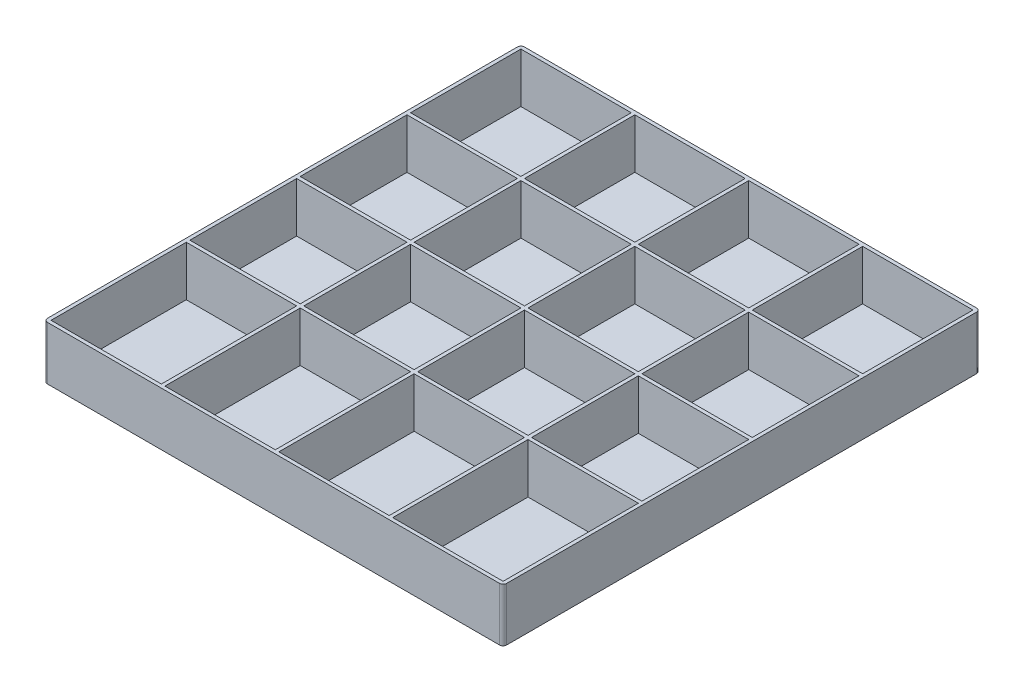
SolidWorks part; units mm, degrees
ref_plane "前视基准面" through (0, 0, 0) normal (0, 0, 1) x (1, 0, 0)
ref_plane "上视基准面" through (0, 0, 0) normal (0, 1, 0) x (1, 0, 0)
ref_plane "右视基准面" through (0, 0, 0) normal (1, 0, 0) x (0, 0, -1)
other "Configuration Table"
sketch "草图1" plane through (0, 0, 0) normal (0, 1, 0) x (1, 0, 0)
  line L1 (129, -134) -> (-129, -134)
  line L2 (129, -134) -> (129, 134)
  line L3 (129, 134) -> (-129, 134)
  line L4 (-129, -134) -> (-129, 134)
  line L5 (129, -134) -> (-129, 134) construction
  line L6 (129, 134) -> (-129, -134) construction
  point P0 (0, 0)
  dimension "D1" = 258
  dimension "D2" = 268
extrude "凸台-拉伸1" add sketch "草图1" along normal blind 2
sketch "草图2" plane through (0, 2, 0) normal (0, 1, 0) x (1, 0, 0)
  line L0 (127, 132) -> (-127, 132)
  line L1 (-127, 132) -> (-127, -132)
  line L2 (-127, -132) -> (127, -132)
  line L3 (127, -132) -> (127, 132)
  line L4 (-129, 134) -> (-129, -134)
  line L5 (-129, -134) -> (129, -134)
  line L6 (129, -134) -> (129, 134)
  line L7 (129, 134) -> (-129, 134)
  line L8 (-129, 134) -> (-129, -134)
  line L9 (-129, -134) -> (129, -134)
  line L10 (129, -134) -> (129, 134)
  line L11 (129, 134) -> (-129, 134)
  dimension "D1" = 0
  dimension "D2" = 2
extrude "凸台-拉伸2" add sketch "草图2" along normal blind 28
sketch "草图3" plane through (0, 2, 0) normal (0, 1, 0) x (1, 0, 0)
  line L0 (-65, 132) -> (-65, -132)
  line L1 (-63, 132) -> (-63, -132)
  line L2 (-127, 132) -> (-127, -132) construction
  line L4 (127, -132) -> (127, 132)
  line L5 (127, 132) -> (-127, 132)
  line L6 (-127, 132) -> (-127, -132)
  line L7 (-127, -132) -> (127, -132)
  line L9 (-63, 132) -> (-65, 132)
  line L11 (-65, -132) -> (-63, -132)
  dimension "D2" = 62
  dimension "D3" = 2
  dimension "D1" = 0
extrude "凸台-拉伸3" add sketch "草图3" along normal blind 28
pattern_linear "阵列(线性)1" count 3 spacing 64 along (1, 0, 0) of "凸台-拉伸3"
sketch "草图4" plane through (0, 2, 0) normal (0, 1, 0) x (1, 0, 0)
  line L0 (-127, 70) -> (127, 70)
  line L1 (-127, 68) -> (127, 68)
  line L2 (127, 132) -> (65, 132) construction
  line L3 (-127, 132) -> (-127, -132) construction
  line L12 (-127, 70) -> (-127, 68)
  line L15 (127, -132) -> (127, 132)
  line L16 (127, 68) -> (127, 70)
  line L17 (127, 132) -> (65, 132)
  line L18 (65, 132) -> (65, -132)
  line L20 (65, -132) -> (127, -132)
  dimension "D2" = 62
  dimension "D3" = 2
  dimension "D1" = 0
extrude "凸台-拉伸5" add sketch "草图4" along normal blind 28
pattern_linear "阵列(线性)2" count 3 spacing 62 along (0, 0, 1) of "凸台-拉伸5"
fillet "圆角1" radius 2 4 edges at (129, 15, -134) (129, 15, 134) (-129, 15, 134) (-129, 15, -134)
